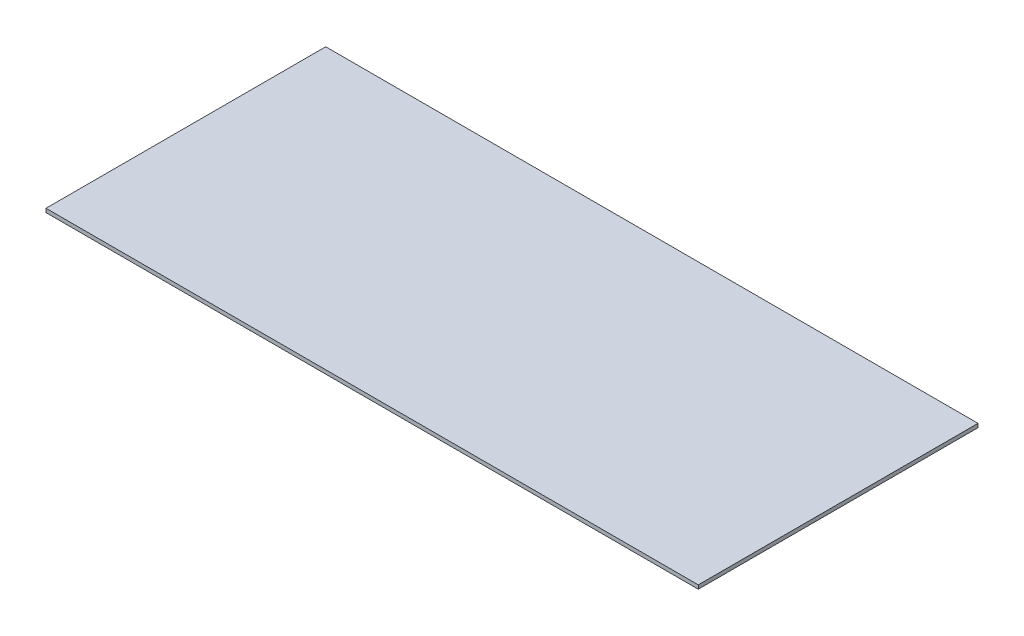
SolidWorks part; units mm, degrees
ref_plane "Front Plane" through (0, 0, 0) normal (0, 0, 1) x (1, 0, 0)
ref_plane "Top Plane" through (0, 0, 0) normal (0, 1, 0) x (1, 0, 0)
ref_plane "Right Plane" through (0, 0, 0) normal (1, 0, 0) x (0, 0, -1)
sketch "Sketch1" plane through (0, 0, 0) normal (0, 1, 0) x (1, 0, 0)
  line L1 (-192.15, 82.4) -> (192.15, 82.4)
  line L2 (-192.15, 82.4) -> (-192.15, -82.4)
  line L3 (-192.15, -82.4) -> (192.15, -82.4)
  line L4 (192.15, 82.4) -> (192.15, -82.4)
  line L5 (-192.15, 82.4) -> (192.15, -82.4) construction
  line L6 (-192.15, -82.4) -> (192.15, 82.4) construction
  point P0 (0, 0)
  dimension "D1" = 384.3
  dimension "D2" = 164.8
extrude "Boss-Extrude1" add sketch "Sketch1" along normal blind 2.2438
